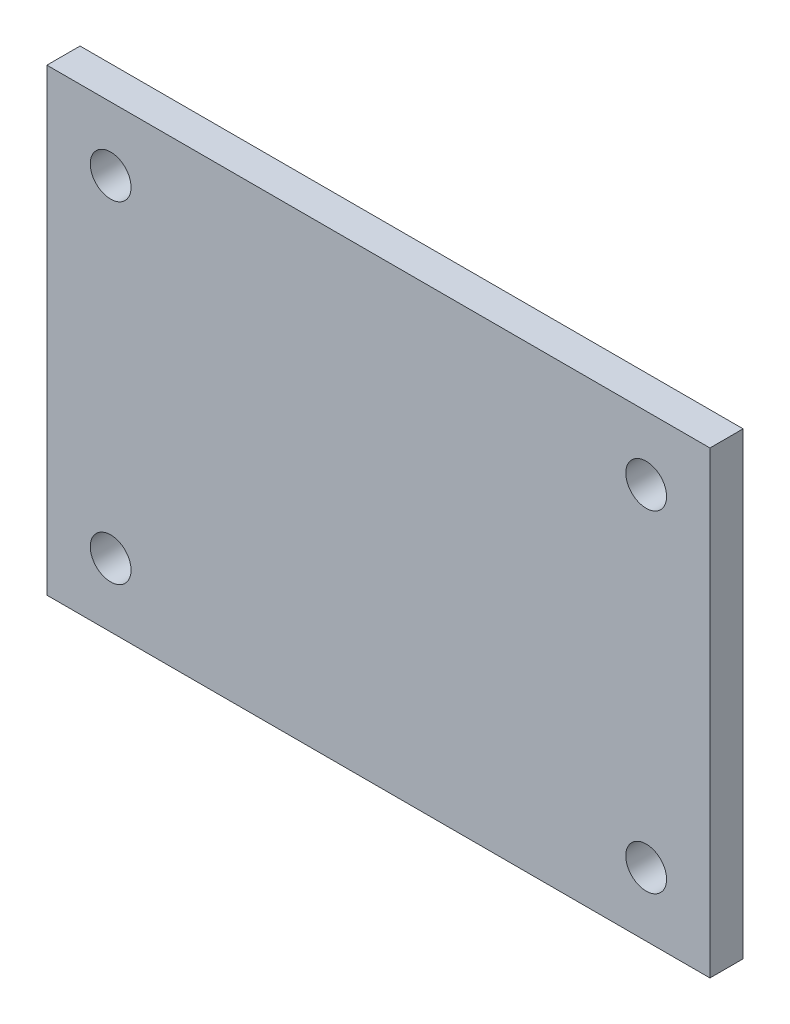
SolidWorks part; units mm, degrees
ref_plane "Front Plane" through (0, 0, 0) normal (0, 0, 1) x (1, 0, 0)
ref_plane "Top Plane" through (0, 0, 0) normal (0, 1, 0) x (1, 0, 0)
ref_plane "Right Plane" through (0, 0, 0) normal (1, 0, 0) x (0, 0, -1)
sketch "Esquisse1" plane through (0, 0, 0) normal (0, 0, 1) x (1, 0, 0)
  line L1 (-10.5, 6.5) -> (10.5, 6.5) construction
  line L2 (-10.5, 6.5) -> (-10.5, -6.5) construction
  line L3 (-10.5, -6.5) -> (10.5, -6.5) construction
  line L4 (10.5, 6.5) -> (10.5, -6.5) construction
  line L5 (-10.5, 6.5) -> (10.5, -6.5) construction
  line L6 (-10.5, -6.5) -> (10.5, 6.5) construction
  line L7 (-13, 9) -> (13, 9)
  line L8 (-13, 9) -> (-13, -9)
  line L9 (-13, -9) -> (13, -9)
  line L10 (13, 9) -> (13, -9)
  line L11 (-13, 9) -> (13, -9) construction
  line L12 (-13, -9) -> (13, 9) construction
  point P0 (0, 0)
  point P6 (0, 0)
  dimension "D1" = 21
  dimension "D2" = 13
  dimension "D3" = 26
  dimension "D4" = 18
extrude "Boss.-Extru.1" add sketch "Esquisse1" along normal blind 1.3
sketch "Esquisse2" plane through (0, 0, 1.3) normal (0, 0, 1) x (1, 0, 0)
  line L1 (-10.5, 6.5) -> (10.5, 6.5) construction
  line L2 (-10.5, 6.5) -> (-10.5, -6.5) construction
  line L3 (-10.5, -6.5) -> (10.5, -6.5) construction
  line L4 (10.5, 6.5) -> (10.5, -6.5) construction
  line L5 (-10.5, 6.5) -> (10.5, -6.5) construction
  line L6 (-10.5, -6.5) -> (10.5, 6.5) construction
  circle A0 centre (-10.5, 6.5) radius 0.45
  circle A1 centre (10.5, 6.5) radius 0.45
  circle A2 centre (10.5, -6.5) radius 0.45
  circle A3 centre (-10.5, -6.5) radius 0.45
  point P0 (0, 0)
  dimension "D1" = 21
  dimension "D2" = 13
  dimension "D3" = 0.9
  dimension "D4" = 0.9
  dimension "D5" = 0.9
  dimension "D6" = 0.9
hole_wizard "Trou taraudé M2x0.41" positions "Esquisse3D1" profile "Esquisse3" tap size "M2x0.4" standard "Ansi Metric"
sketch3d "Esquisse3D1"
  point P0 (-10.5, 6.5, 1.3)
  point P3 (-10.5, -6.5, 1.3)
  point P6 (10.5, -6.5, 1.3)
  point P9 (10.5, 6.5, 1.3)
sketch "Esquisse3" plane through (-10.5, 6.5, 1.3) normal (1, 0, 0) x (0, -1, 0)
  line L0 (0, 0) -> (0, 1.7807)
  line L1 (0, 1.7807) -> (0.8, 1.3)
  line L2 (0.8, 1.3) -> (0.8, 0)
  line L5 (0.8, 0) -> (0, 0)
  line L10 (0, 1.7807) -> (-0.8, 1.3) construction
  line L11 (0, -6.35) -> (0, 107.95) construction
  dimension "Diamètre du trou pour taraudage" = 1.6
  dimension "Profondeur du trou pour taraudage" = 1.3
  dimension "Angle de pointe" = 118
cosmetic thread "Filetage de perçage1" parameters "D1"=130, "D2"=2
cosmetic thread "Filetage de perçage2" parameters "D1"=130, "D2"=2
cosmetic thread "Filetage de perçage3" parameters "D1"=130, "D2"=2
cosmetic thread "Filetage de perçage4" parameters "D1"=130, "D2"=2
equation "\"D3@Esquisse1\"=\"D1@Esquisse1\"+5mm"
equation "\"D4@Esquisse1\"=\"D2@Esquisse1\"+5mm"
equation "\"D4@Esquisse2\"=\"D3@Esquisse2\""
